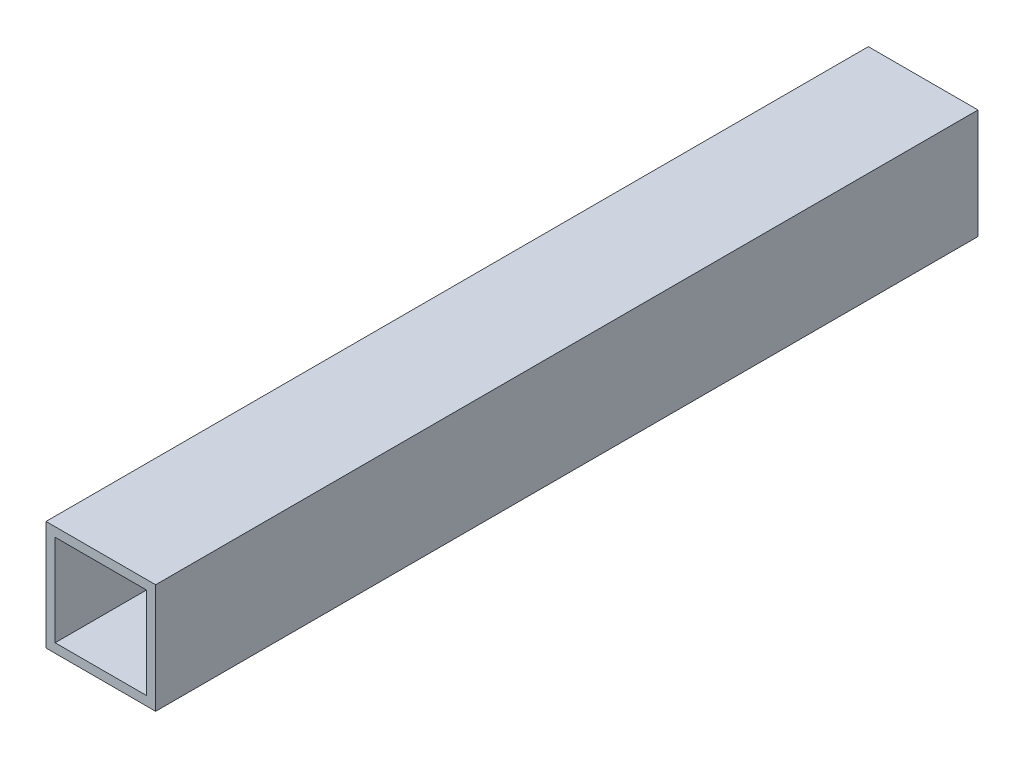
SolidWorks part; units mm, degrees
ref_plane "前视基准面" through (0, 0, 0) normal (0, 0, 1) x (1, 0, 0)
ref_plane "上视基准面" through (0, 0, 0) normal (0, 1, 0) x (1, 0, 0)
ref_plane "右视基准面" through (0, 0, 0) normal (1, 0, 0) x (0, 0, -1)
sketch "草图1" plane through (0, 0, 0) normal (0, 0, 1) x (1, 0, 0)
  line L0 (-12, 12) -> (12, 12)
  line L1 (-10, 10) -> (10, 10)
  line L2 (-10, 10) -> (-10, -10)
  line L3 (-10, -10) -> (10, -10)
  line L4 (10, 10) -> (10, -10)
  line L5 (-10, 10) -> (10, -10) construction
  line L6 (-10, -10) -> (10, 10) construction
  line L7 (12, 12) -> (12, -12)
  line L8 (-12, -12) -> (12, -12)
  line L9 (-12, 12) -> (-12, -12)
  point P0 (0, 0)
  dimension "D1" = 20
  dimension "D2" = 20
  dimension "D3" = 2
extrude "凸台-拉伸1" add sketch "草图1" along normal blind 180
